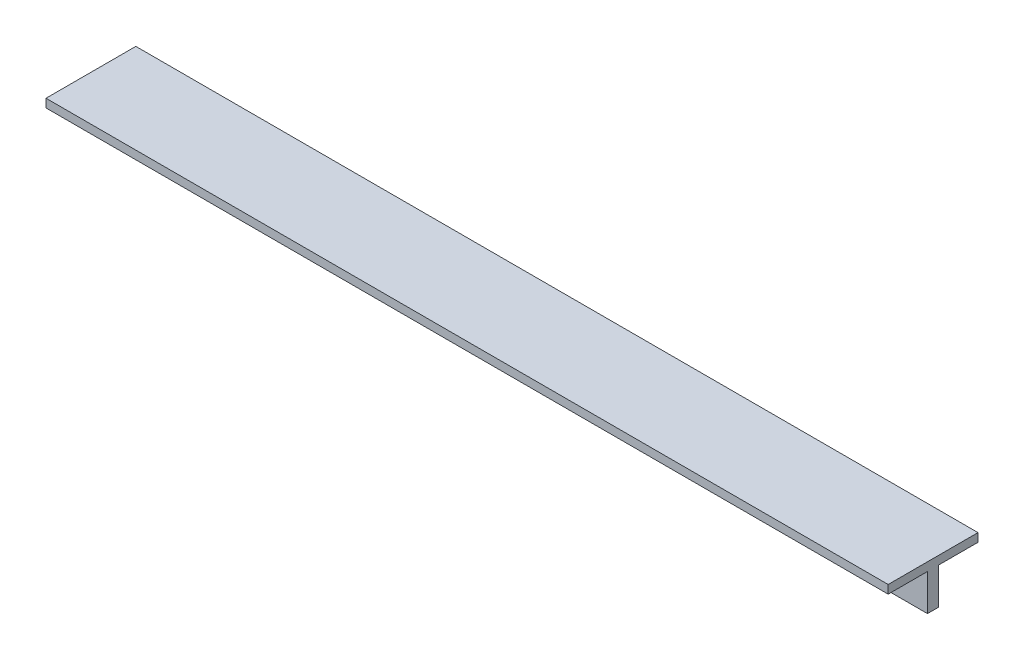
SolidWorks part; units mm, degrees
ref_plane "Front Plane" through (0, 0, 0) normal (0, 0, 1) x (1, 0, 0)
ref_plane "Top Plane" through (0, 0, 0) normal (0, 1, 0) x (1, 0, 0)
ref_plane "Right Plane" through (0, 0, 0) normal (1, 0, 0) x (0, 0, -1)
sketch "Sketch1" plane through (0, 0, 0) normal (1, 0, 0) x (0, 0, -1)
  line L0 (0, 0) -> (0, -8)
  line L1 (0, -8) -> (1, -8)
  line L2 (1, -8) -> (1, -1.5)
  line L3 (1, -1.5) -> (8, -1.5)
  line L4 (8, -1.5) -> (8, 0)
  line L5 (8, 0) -> (0, 0)
  dimension "D1" = 1
  dimension "D2" = 8
  dimension "D3" = 8
  dimension "D4" = 1.5
extrude "Boss-Extrude1" add sketch "Sketch1" along normal mid plane 150
mirror "Mirror2" about plane through (75, 0, 0) normal (0, 0, -1) of bodies 103
equation "\"D4@Sketch1\"=1.5mm"
